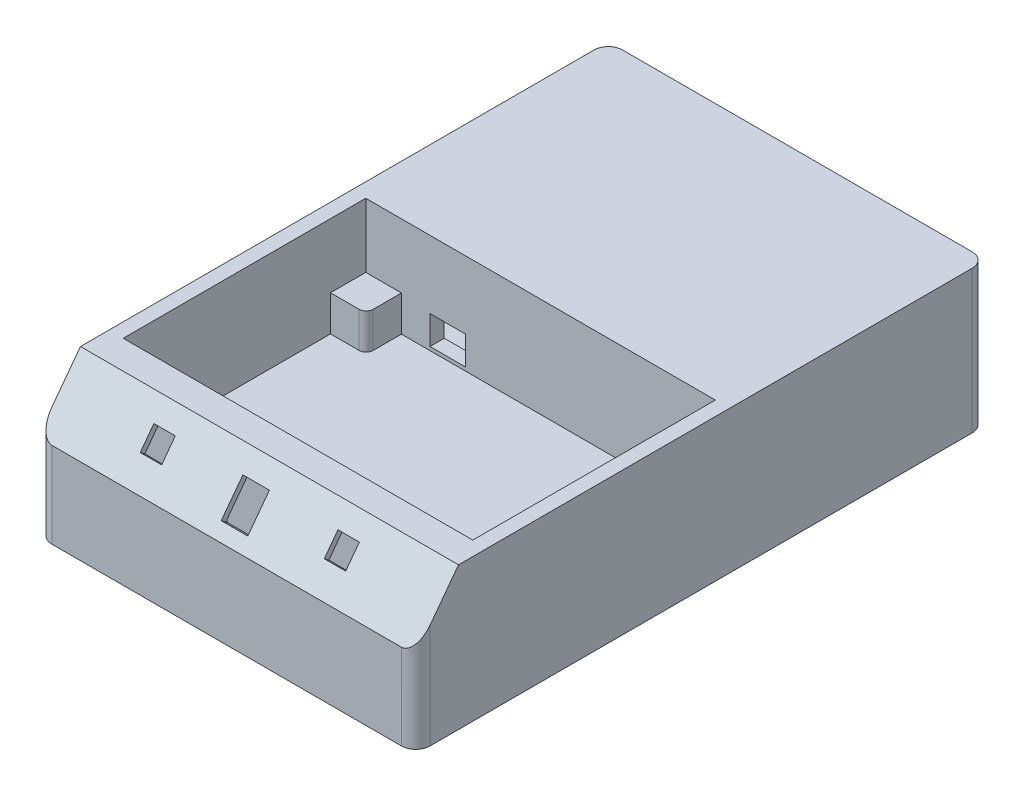
SolidWorks part; units mm, degrees
ref_plane "Front Plane" through (0, 0, 0) normal (0, 0, 1) x (1, 0, 0)
ref_plane "Top Plane" through (0, 0, 0) normal (0, 1, 0) x (1, 0, 0)
ref_plane "Right Plane" through (0, 0, 0) normal (1, 0, 0) x (0, 0, -1)
sketch "Sketch1" plane through (0, 0, 0) normal (0, 1, 0) x (1, 0, 0)
  line L0 (0, -10) -> (0, -390)
  line L1 (10, 0) -> (255, 0)
  line L2 (265, -10) -> (265, -390)
  line L3 (10, -400) -> (255, -400)
  arc A0 (0, -10) -> (10, 0) centre (10, -10) cw
  arc A1 (265, -10) -> (255, 0) centre (255, -10) ccw
  arc A2 (0, -390) -> (10, -400) centre (10, -390) ccw
  arc A3 (265, -390) -> (255, -400) centre (255, -390) cw
extrude "Boss-Extrude2" add sketch "Sketch1" along normal blind 100
ref_plane "Plane1" through (0, 100, 0) normal (0, 1, 0) x (1, 0, 0)
sketch "Sketch4" plane through (0, 100, 0) normal (0, 1, 0) x (1, 0, 0)
  line L0 (0, -10) -> (0, -390) construction
  line L1 (10, -180) -> (255, -180)
  line L2 (10, -180) -> (10, -350)
  line L3 (10, -350) -> (255, -350)
  line L4 (255, -180) -> (255, -350)
  line L5 (10, -400) -> (255, -400) construction
  dimension "D1" = 170
  dimension "D2" = 245
  dimension "D3" = 10
  dimension "D4" = 50
extrude "Cut-Extrude2" cut sketch "Sketch4" against normal blind 70
ref_plane "Plane2" through (132.5, 0, 0) normal (1, 0, 0) x (0, 0, -1)
ref_plane "Plane4" through (0, 0, 360) normal (0, 0, 1) x (1, 0, 0)
sketch "Sketch10" plane through (132.5, 0, 0) normal (1, 0, 0) x (0, 0, -1)
  line L0 (-400, 60) -> (-370, 100)
  line L1 (-400, 100) -> (-400, 0) construction
  line L2 (145.75, 100) -> (-145.75, 100) construction
  line L5 (-360, 55) -> (-360, -55) construction
  line L6 (-400, 60) -> (-400, 100)
  line L7 (-400, 100) -> (-370, 100)
  dimension "D1" = 60
  dimension "D2" = 10
extrude "Cut-Extrude12" cut sketch "Sketch10" against normal through all both and the other way through all
sketch "Sketch14" plane through (132.5, 0, 0) normal (1, 0, 0) x (0, 0, -1)
  line L0 (-390, 10) -> (-360, 10)
  line L1 (-390, 73.3333) -> (-390, 0) construction
  line L2 (-360, 33) -> (-360, -33) construction
  line L7 (-390, 66.6667) -> (-390, 10)
  line L8 (-390, 73.3333) -> (-370, 100) construction
  line L10 (-390, 0) -> (-10, 0) construction
  line L11 (-390, 66.6667) -> (-368, 96)
  line L12 (-368, 96) -> (-360, 96)
  line L13 (-360, 96) -> (-360, 10)
  line L14 (145.75, 100) -> (-145.75, 100) construction
  dimension "D1" = 4
  dimension "D2" = 4
  dimension "D3" = 4
  dimension "D4" = 10
extrude "Cut-Extrude13" cut sketch "Sketch14" against normal mid plane 245
sketch "Sketch15" plane through (132.5, 0, 0) normal (1, 0, 0) x (0, 0, -1)
  line L0 (-360, 33) -> (-360, -33) construction
  line L2 (-360, 9.7841) -> (-360, 20)
  line L3 (-360, 20) -> (-170, 20)
  line L5 (-10, 100) -> (-10, 0) construction
  line L6 (-170, 95) -> (-15, 95)
  line L9 (-15, 95) -> (-15, 10)
  line L11 (-180, 30) -> (-180, 100) construction
  line L12 (145.75, 100) -> (-145.75, 100) construction
  line L13 (-170, 20) -> (-170, 95)
  line L14 (-15, 10) -> (-360, 9.7841)
  dimension "D1" = 10
  dimension "D3" = 5
  dimension "D5" = 10
  dimension "D6" = 5
extrude "Cut-Extrude14" cut sketch "Sketch15" against normal mid plane 245
sketch "Sketch16" plane through (0, 0, 0) normal (0, 0, -1) x (-1, 0, 0)
  line L0 (-240.1407, 77.3029) -> (-190.4678, 77.3029) construction
  line L1 (-240.1407, 79.2382) -> (-190.4678, 79.2382)
  line L2 (-240.1407, 75.3676) -> (-190.4678, 75.3676)
  line L3 (-183.8017, 77.3029) -> (-136.4942, 77.3029) construction
  line L4 (-183.8017, 79.2382) -> (-136.4942, 79.2382)
  line L5 (-183.8017, 75.3676) -> (-136.4942, 75.3676)
  line L6 (-239.9326, 70.4218) -> (-190.2597, 70.4218) construction
  line L7 (-239.9326, 72.3571) -> (-190.2597, 72.3571)
  line L8 (-239.9326, 68.4865) -> (-190.2597, 68.4865)
  line L9 (-183.5936, 70.4218) -> (-136.2861, 70.4218) construction
  line L10 (-183.5936, 72.3571) -> (-136.2861, 72.3571)
  line L11 (-183.5936, 68.4865) -> (-136.2861, 68.4865)
  line L12 (-239.8251, 63.5407) -> (-190.1522, 63.5407) construction
  line L13 (-239.8251, 65.476) -> (-190.1522, 65.476)
  line L14 (-239.8251, 61.6054) -> (-190.1522, 61.6054)
  line L15 (-183.4861, 63.5407) -> (-136.1786, 63.5407) construction
  line L16 (-183.4861, 65.476) -> (-136.1786, 65.476)
  line L17 (-183.4861, 61.6054) -> (-136.1786, 61.6054)
  line L18 (-239.617, 56.6596) -> (-189.9441, 56.6596) construction
  line L19 (-239.617, 58.5949) -> (-189.9441, 58.5949)
  line L20 (-239.617, 54.7243) -> (-189.9441, 54.7243)
  line L21 (-183.278, 56.6596) -> (-135.9705, 56.6596) construction
  line L22 (-183.278, 58.5949) -> (-135.9705, 58.5949)
  line L23 (-183.278, 54.7243) -> (-135.9705, 54.7243)
  line L24 (-239.9187, 42.2523) -> (-190.2458, 42.2523) construction
  line L25 (-239.9187, 44.1876) -> (-190.2458, 44.1876)
  line L26 (-239.9187, 40.317) -> (-190.2458, 40.317)
  line L27 (-183.5797, 42.2523) -> (-136.2722, 42.2523) construction
  line L28 (-183.5797, 44.1876) -> (-136.2722, 44.1876)
  line L29 (-183.5797, 40.317) -> (-136.2722, 40.317)
  line L30 (-239.7106, 35.3712) -> (-190.0377, 35.3712) construction
  line L31 (-239.7106, 37.3065) -> (-190.0377, 37.3065)
  line L32 (-239.7106, 33.4359) -> (-190.0377, 33.4359)
  line L33 (-183.3716, 35.3712) -> (-136.0641, 35.3712) construction
  line L34 (-183.3716, 37.3065) -> (-136.0641, 37.3065)
  line L35 (-183.3716, 33.4359) -> (-136.0641, 33.4359)
  line L36 (-239.6031, 28.4901) -> (-189.9302, 28.4901) construction
  line L37 (-239.6031, 30.4254) -> (-189.9302, 30.4254)
  line L38 (-239.6031, 26.5548) -> (-189.9302, 26.5548)
  line L39 (-183.2641, 28.4901) -> (-135.9566, 28.4901) construction
  line L40 (-183.2641, 30.4254) -> (-135.9566, 30.4254)
  line L41 (-183.2641, 26.5548) -> (-135.9566, 26.5548)
  line L42 (-239.395, 21.609) -> (-189.7221, 21.609) construction
  line L43 (-239.395, 23.5443) -> (-189.7221, 23.5443)
  line L44 (-239.395, 19.6737) -> (-189.7221, 19.6737)
  line L45 (-183.056, 21.609) -> (-135.7485, 21.609) construction
  line L46 (-183.056, 23.5443) -> (-135.7485, 23.5443)
  line L47 (-183.056, 19.6737) -> (-135.7485, 19.6737)
  line L48 (-10, 10) -> (-255, 10) construction
  line L49 (-83.9668, 10) -> (-40.8281, 10)
  line L50 (-83.9668, 10) -> (-83.9668, 50.3794)
  line L51 (-83.9668, 50.3794) -> (-40.8281, 50.3794)
  line L52 (-40.8281, 10) -> (-40.8281, 50.3794)
  arc A0 (-240.1407, 79.2382) -> (-240.1407, 75.3676) centre (-240.1407, 77.3029) ccw
  arc A1 (-190.4678, 75.3676) -> (-190.4678, 79.2382) centre (-190.4678, 77.3029) ccw
  arc A2 (-183.8017, 79.2382) -> (-183.8017, 75.3676) centre (-183.8017, 77.3029) ccw
  arc A3 (-136.4942, 75.3676) -> (-136.4942, 79.2382) centre (-136.4942, 77.3029) ccw
  arc A4 (-239.9326, 72.3571) -> (-239.9326, 68.4865) centre (-239.9326, 70.4218) ccw
  arc A5 (-190.2597, 68.4865) -> (-190.2597, 72.3571) centre (-190.2597, 70.4218) ccw
  arc A6 (-183.5936, 72.3571) -> (-183.5936, 68.4865) centre (-183.5936, 70.4218) ccw
  arc A7 (-136.2861, 68.4865) -> (-136.2861, 72.3571) centre (-136.2861, 70.4218) ccw
  arc A8 (-239.8251, 65.476) -> (-239.8251, 61.6054) centre (-239.8251, 63.5407) ccw
  arc A9 (-190.1522, 61.6054) -> (-190.1522, 65.476) centre (-190.1522, 63.5407) ccw
  arc A10 (-183.4861, 65.476) -> (-183.4861, 61.6054) centre (-183.4861, 63.5407) ccw
  arc A11 (-136.1786, 61.6054) -> (-136.1786, 65.476) centre (-136.1786, 63.5407) ccw
  arc A12 (-239.617, 58.5949) -> (-239.617, 54.7243) centre (-239.617, 56.6596) ccw
  arc A13 (-189.9441, 54.7243) -> (-189.9441, 58.5949) centre (-189.9441, 56.6596) ccw
  arc A14 (-183.278, 58.5949) -> (-183.278, 54.7243) centre (-183.278, 56.6596) ccw
  arc A15 (-135.9705, 54.7243) -> (-135.9705, 58.5949) centre (-135.9705, 56.6596) ccw
  arc A16 (-239.9187, 44.1876) -> (-239.9187, 40.317) centre (-239.9187, 42.2523) ccw
  arc A17 (-190.2458, 40.317) -> (-190.2458, 44.1876) centre (-190.2458, 42.2523) ccw
  arc A18 (-183.5797, 44.1876) -> (-183.5797, 40.317) centre (-183.5797, 42.2523) ccw
  arc A19 (-136.2722, 40.317) -> (-136.2722, 44.1876) centre (-136.2722, 42.2523) ccw
  arc A20 (-239.7106, 37.3065) -> (-239.7106, 33.4359) centre (-239.7106, 35.3712) ccw
  arc A21 (-190.0377, 33.4359) -> (-190.0377, 37.3065) centre (-190.0377, 35.3712) ccw
  arc A22 (-183.3716, 37.3065) -> (-183.3716, 33.4359) centre (-183.3716, 35.3712) ccw
  arc A23 (-136.0641, 33.4359) -> (-136.0641, 37.3065) centre (-136.0641, 35.3712) ccw
  arc A24 (-239.6031, 30.4254) -> (-239.6031, 26.5548) centre (-239.6031, 28.4901) ccw
  arc A25 (-189.9302, 26.5548) -> (-189.9302, 30.4254) centre (-189.9302, 28.4901) ccw
  arc A26 (-183.2641, 30.4254) -> (-183.2641, 26.5548) centre (-183.2641, 28.4901) ccw
  arc A27 (-135.9566, 26.5548) -> (-135.9566, 30.4254) centre (-135.9566, 28.4901) ccw
  arc A28 (-239.395, 23.5443) -> (-239.395, 19.6737) centre (-239.395, 21.609) ccw
  arc A29 (-189.7221, 19.6737) -> (-189.7221, 23.5443) centre (-189.7221, 21.609) ccw
  arc A30 (-183.056, 23.5443) -> (-183.056, 19.6737) centre (-183.056, 21.609) ccw
  arc A31 (-135.7485, 19.6737) -> (-135.7485, 23.5443) centre (-135.7485, 21.609) ccw
  point P2 (-215.3042, 77.3029)
  point P9 (-160.1479, 77.3029)
  point P26 (-215.0961, 70.4218)
  point P33 (-159.9399, 70.4218)
  point P40 (-214.9886, 63.5407)
  point P47 (-159.8323, 63.5407)
  point P54 (-214.7805, 56.6596)
  point P61 (-159.6243, 56.6596)
  point P68 (-215.0822, 42.2523)
  point P75 (-159.926, 42.2523)
  point P82 (-214.8742, 35.3712)
  point P89 (-159.7179, 35.3712)
  point P96 (-214.7666, 28.4901)
  point P103 (-159.6104, 28.4901)
  point P110 (-214.5586, 21.609)
  point P117 (-159.4023, 21.609)
extrude "Cut-Extrude15" cut sketch "Sketch16" against normal blind 30
sketch "Sketch17" plane through (0, 213.6, 284.8) normal (0, 0.6, 0.8) x (1, 0, 0)
  line L0 (132.5, -55) -> (132.5, 55) construction
  line L1 (60.5, -157) -> (75.5, -157)
  line L2 (60.5, -157) -> (60.5, -173)
  line L3 (60.5, -173) -> (75.5, -173)
  line L4 (75.5, -157) -> (75.5, -173)
  line L5 (189.5, -157) -> (204.5, -157)
  line L6 (189.5, -157) -> (189.5, -173)
  line L7 (189.5, -173) -> (204.5, -173)
  line L8 (204.5, -157) -> (204.5, -173)
  line L9 (0, -142) -> (265, -142) construction
  line L11 (122.837, -157) -> (141.4592, -157)
  line L12 (122.837, -157) -> (122.837, -182.2735)
  line L13 (122.837, -182.2735) -> (141.4592, -182.2735)
  line L14 (141.4592, -157) -> (141.4592, -182.2735)
  dimension "D1" = 16
  dimension "D2" = 15
  dimension "D3" = 16
  dimension "D4" = 57
  dimension "D5" = 57
  dimension "D6" = 15
  dimension "D7" = 15
  dimension "D8" = 15
extrude "Cut-Extrude16" cut sketch "Sketch17" against normal blind 10
sketch "Sketch18" plane through (0, 30, 0) normal (0, 1, 0) x (1, 0, 0)
  line L0 (10, -180) -> (10, -204.7299)
  line L1 (10, -180) -> (10, -350) construction
  line L2 (10, -204.7299) -> (30, -204.7299)
  line L3 (10, -180) -> (34.9927, -180)
  line L4 (34.9927, -180) -> (34.9927, -200)
  line L5 (255, -350) -> (255, -324.1491)
  line L6 (255, -350) -> (255, -180) construction
  line L7 (255, -324.1491) -> (235, -324.1491)
  line L8 (255, -350) -> (230.0729, -350)
  line L9 (10, -350) -> (255, -350) construction
  line L10 (230.0729, -350) -> (230.0729, -330)
  arc A0 (30, -204.7299) -> (34.9927, -200) centre (30, -199.7299) ccw
  arc A1 (235, -324.1491) -> (230.0729, -330) centre (235, -329.1491) ccw
  point P22 (0, 0)
  dimension "D1" = 5
  dimension "D2" = 20
  dimension "D3" = 20
  dimension "D4" = 5
  dimension "D5" = 20
  dimension "D6" = 20
extrude "Boss-Extrude3" add sketch "Sketch18" along normal blind 25
sketch "Sketch19" plane through (0, 0, 180) normal (0, 0, 1) x (1, 0, 0)
  line L0 (10, 55) -> (30, 55) construction
  line L3 (54.9927, 52.5) -> (79.9927, 52.5)
  line L5 (54.9927, 32.5) -> (79.9927, 32.5)
  line L6 (54.9927, 52.5) -> (54.9927, 32.5)
  line L7 (79.9927, 32.5) -> (79.9927, 52.5)
  line L8 (10, 30) -> (230.0729, 30) construction
  line L9 (34.9927, 55) -> (34.9927, 30) construction
  point P7 (0, 0)
  dimension "D1" = 2.5
  dimension "D2" = 2.5
  dimension "D3" = 25
  dimension "D4" = 20
extrude "Cut-Extrude17" cut sketch "Sketch19" against normal blind 15
